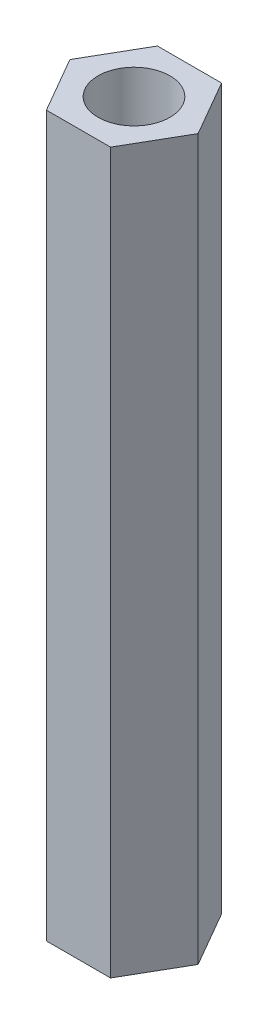
SolidWorks part; units mm, degrees
ref_plane "Front Plane" through (0, 0, 0) normal (0, 0, 1) x (1, 0, 0)
ref_plane "Top Plane" through (0, 0, 0) normal (0, 1, 0) x (1, 0, 0)
ref_plane "Right Plane" through (0, 0, 0) normal (1, 0, 0) x (0, 0, -1)
sketch "Sketch1" plane through (0, 0, 0) normal (0, 1, 0) x (1, 0, 0)
  line L1 (2.6731, 0) -> (1.3366, 2.315)
  line L2 (1.3366, 2.315) -> (-1.3366, 2.315)
  line L3 (-1.3366, 2.315) -> (-2.6731, 0)
  line L4 (-2.6731, 0) -> (-1.3366, -2.315)
  line L5 (-1.3366, -2.315) -> (1.3366, -2.315)
  line L6 (1.3366, -2.315) -> (2.6731, 0)
  circle A0 centre (0, 0) radius 2.315 construction
  circle A1 centre (0, 0) radius 1.5
  dimension "D2" = 3
  dimension "D1" = 4.63
extrude "Boss-Extrude1" add sketch "Sketch1" along normal blind 30
